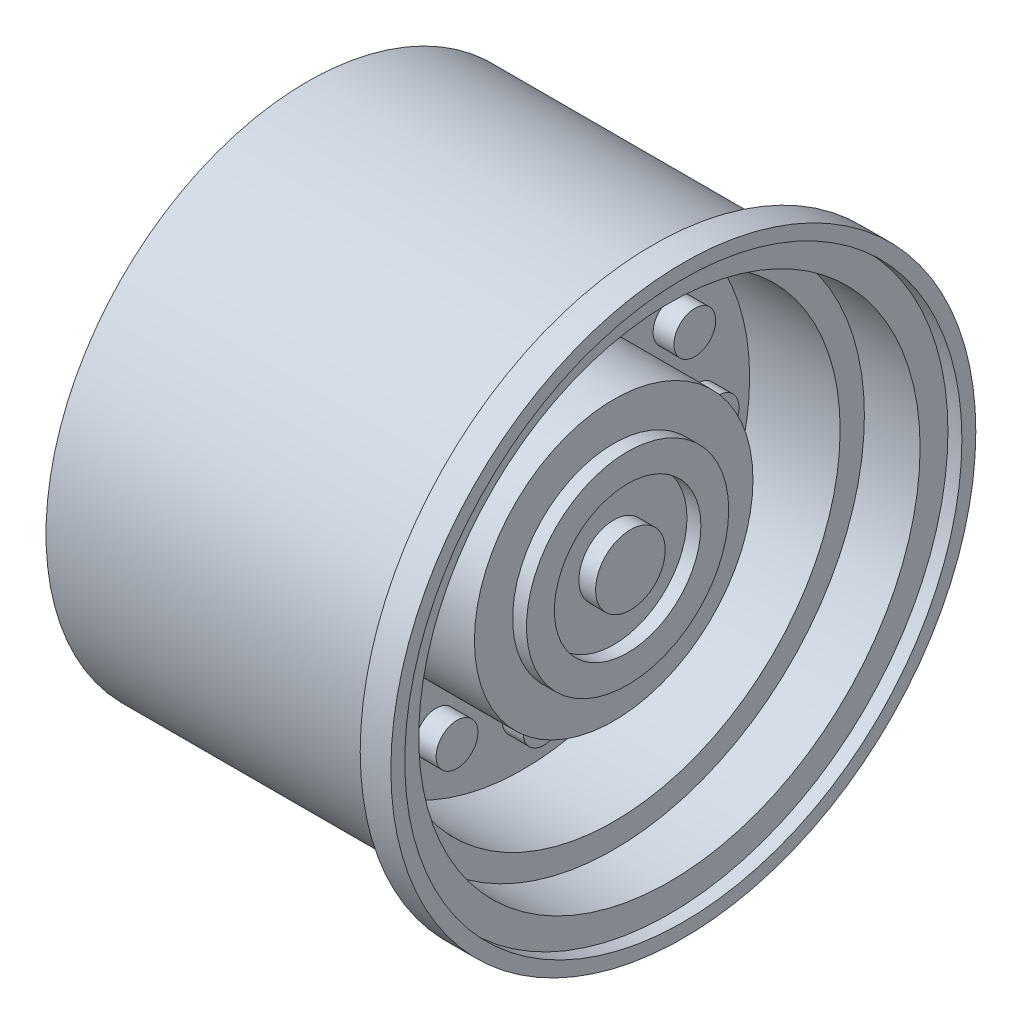
SolidWorks part; units mm, degrees
ref_plane "Front Plane" through (0, 0, 0) normal (0, 0, 1) x (1, 0, 0)
ref_plane "Top Plane" through (0, 0, 0) normal (0, 1, 0) x (1, 0, 0)
ref_plane "Right Plane" through (0, 0, 0) normal (1, 0, 0) x (0, 0, -1)
sketch "Sketch1" plane through (0, 0, 0) normal (0, 0, 1) x (1, 0, 0)
  line L0 (0, 9.38) -> (0, 0) construction
  line L1 (0, 0) -> (2.6312, 0) construction
  line L2 (0, 0) -> (-4.56, 0)
  line L3 (-4.56, 0) -> (-4.56, 3.25)
  line L4 (-4.56, 3.25) -> (-3.81, 3.25)
  line L5 (-3.81, 3.25) -> (-3.81, 4.5)
  line L6 (-3.81, 4.5) -> (-2.91, 4.5)
  line L7 (-2.91, 4.5) -> (-2.91, 8.13)
  line L8 (-2.91, 8.13) -> (-5.31, 8.13)
  line L9 (-5.31, 8.13) -> (-5.31, 8.5)
  line L10 (-5.31, 8.5) -> (-6.81, 8.5)
  line L11 (-6.81, 8.5) -> (-6.81, 9.38)
  line L12 (-6.81, 9.38) -> (5.59, 9.38)
  line L13 (5.59, 9.38) -> (5.59, 10.5)
  line L14 (5.59, 10.5) -> (6.69, 10.5)
  line L15 (6.69, 10.5) -> (6.69, 10)
  line L16 (6.69, 10) -> (6.19, 10)
  line L17 (6.19, 10) -> (6.19, 9)
  line L18 (6.19, 9) -> (4.19, 9)
  line L19 (4.19, 9) -> (4.19, 8.13)
  line L20 (4.19, 8.13) -> (0.94, 8.13)
  line L21 (0.94, 8.13) -> (0.94, 5)
  line L22 (0.94, 5) -> (4.19, 5)
  line L23 (4.19, 5) -> (4.19, 3.63)
  line L24 (4.19, 3.63) -> (4.69, 3.63)
  line L25 (4.69, 3.63) -> (4.69, 0)
  line L26 (4.69, 0) -> (0, 0)
  point P8 (-2.0234, 4.8051)
  dimension "D1" = 0.5
  dimension "D2" = 5
  dimension "D3" = 3.63
  dimension "D4" = 0.94
  dimension "D5" = 8.13
  dimension "D6" = 9
  dimension "D7" = 10
  dimension "D8" = 10.5
  dimension "D9" = 9.38
  dimension "D10" = 8.5
  dimension "D11" = 8.13
  dimension "D12" = 4.5
  dimension "D13" = 3.25
  dimension "D14" = 5.75
  dimension "D15" = 13.5
  dimension "D16" = 1.5
  dimension "D17" = 3.9
  dimension "D18" = 1.1
  dimension "D19" = 0.5
  dimension "D20" = 2.5
  dimension "D21" = 2.25
  dimension "D22" = 3
revolve "Revolve2" add sketch "Sketch1" angle 360 about L26
sketch "Sketch2" plane through (0.94, 0, 0) normal (1, 0, 0) x (0, 0, -1)
  circle A0 centre (0, 0) radius 6.25 construction
  circle A1 centre (0, 6.25) radius 0.75
  circle A2 centre (3.125, 5.4127) radius 0.75
  circle A3 centre (5.4127, 3.125) radius 0.75
  circle A4 centre (6.25, 0) radius 0.75
  circle A5 centre (5.4127, -3.125) radius 0.75
  circle A6 centre (3.125, -5.4127) radius 0.75
  circle A7 centre (0, -6.25) radius 0.75
  circle A8 centre (-3.125, -5.4127) radius 0.75
  circle A9 centre (-5.4127, -3.125) radius 0.75
  circle A10 centre (-6.25, 0) radius 0.75
  circle A11 centre (-5.4127, 3.125) radius 0.75
  circle A12 centre (-3.125, 5.4127) radius 0.75
  point P29 (0, 0)
  dimension "D1" = 12.5
  dimension "D2" = 1.5
  dimension "D3" = 12
extrude "Boss-Extrude1" add sketch "Sketch2" along normal blind 0.75
sketch "Sketch3" plane through (4.69, 0, 0) normal (1, 0, 0) x (0, 0, -1)
  circle A0 centre (0, 0) radius 2.63
  circle A1 centre (0, 0) radius 3.63 construction
  dimension "D1" = 1
extrude "Cut-Extrude1" cut sketch "Sketch3" against normal blind 0.5
sketch "Sketch4" plane through (4.19, 0, 0) normal (1, 0, 0) x (0, 0, -1)
  circle A0 centre (0, 0) radius 1.25
  dimension "D1" = 2.5
extrude "Boss-Extrude2" add sketch "Sketch4" along normal blind 0.6
sketch "Sketch5" plane through (-4.56, 0, 0) normal (-1, 0, 0) x (0, 0, 1)
  circle A0 centre (0, 0) radius 1.25
  dimension "D1" = 2.5
extrude "Cut-Extrude2" cut sketch "Sketch5" against normal blind 5
